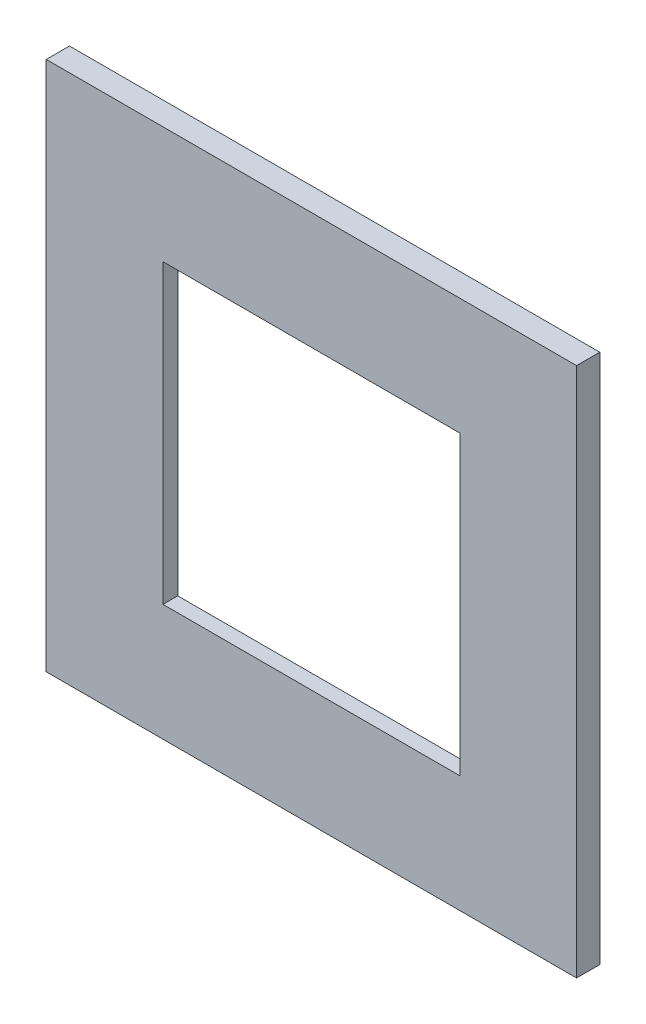
SolidWorks part; units mm, degrees
ref_plane "Front Plane" through (0, 0, 0) normal (0, 0, 1) x (1, 0, 0)
ref_plane "Top Plane" through (0, 0, 0) normal (0, 1, 0) x (1, 0, 0)
ref_plane "Right Plane" through (0, 0, 0) normal (1, 0, 0) x (0, 0, -1)
sketch "Sketch1" plane through (0, 0, 0) normal (0, 1, 0) x (1, 0, 0)
  line L1 (41.1, 3.6) -> (-41.1, 3.6)
  line L2 (41.1, 3.6) -> (41.1, 0)
  line L3 (-41.1, 3.6) -> (-41.1, 0)
  line L5 (0, -1.941) -> (0, 24.0569) construction
  line L9 (-41.1, 0) -> (41.1, 0)
  point P19 (0, 0)
  dimension "D2" = 82.2
  dimension "D5" = 3.6
extrude "Boss-Extrude1" add sketch "Sketch1" along normal blind 82.2
ref_plane "Plane1" through (0, 0, -3.6) normal (0, 0, -1) x (-1, 0, 0)
sketch "Sketch2" plane through (0, 0, -3.6) normal (0, 0, -1) x (-1, 0, 0)
  line L0 (0, 1.98) -> (0, -1.98) construction
  line L1 (38.2, 2.9) -> (-38.2, 2.9)
  line L2 (38.2, 2.9) -> (38.2, 79.3)
  line L3 (38.2, 79.3) -> (-38.2, 79.3)
  line L4 (-38.2, 2.9) -> (-38.2, 79.3)
  line L5 (38.2, 2.9) -> (-38.2, 79.3) construction
  line L6 (38.2, 79.3) -> (-38.2, 2.9) construction
  line L7 (0, 0) -> (0, 82.2) construction
  line L8 (-41.1, 82.2) -> (41.1, 82.2) construction
  point P0 (0, 41.1)
  point P13 (0, 41.1)
  dimension "D1" = 76.4
extrude "Cut-Extrude1" cut sketch "Sketch2" against normal blind 1.31
sketch "Sketch4" plane through (0, 0, -3.6) normal (0, 0, -1) x (-1, 0, 0)
  circle A0 centre (38.2, 2.9) radius 1
  circle A1 centre (38.2, 79.3) radius 1
  circle A2 centre (-38.2, 2.9) radius 1
  circle A3 centre (-38.2, 79.3) radius 1
  dimension "D1" = 2
extrude "Cut-Extrude3" cut sketch "Sketch4" against normal up to surface (1.31 mm away) up to face at (0, 41.1, -2.29)
sketch "Sketch3" plane through (0, 0, -2.29) normal (0, 0, -1) x (-1, 0, 0)
  line L1 (23, 18.1) -> (-23, 18.1)
  line L2 (23, 18.1) -> (23, 64.1)
  line L3 (23, 64.1) -> (-23, 64.1)
  line L4 (-23, 18.1) -> (-23, 64.1)
  line L5 (23, 18.1) -> (-23, 64.1) construction
  line L6 (23, 64.1) -> (-23, 18.1) construction
  point P0 (0, 41.1)
  dimension "D1" = 46
extrude "Cut-Extrude2" cut sketch "Sketch3" against normal through all
sketch "Sketch6" plane through (0, 0, 0) normal (0, 0, 1) x (1, 0, 0)
  line L0 (-41.1, 82.2) -> (41.1, 0) construction
  line L1 (-27.4408, 68.5408) -> (29.0277, 68.5408)
  line L2 (-27.4408, 68.5408) -> (-27.4408, 12.0723)
  line L3 (-27.4408, 12.0723) -> (29.0277, 12.0723)
  line L4 (29.0277, 68.5408) -> (29.0277, 12.0723)
  point P8 (0, 0)
  point P9 (0, 0)
